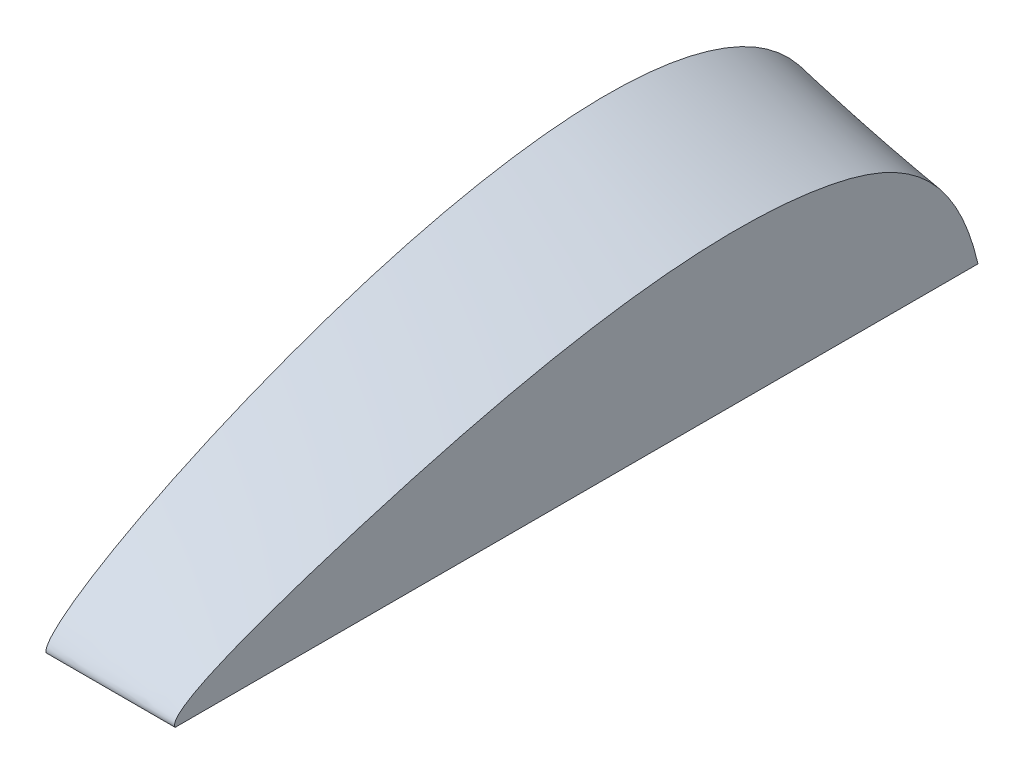
SolidWorks part; units mm, degrees
ref_plane "Front Plane" through (0, 0, 0) normal (0, 0, 1) x (1, 0, 0)
ref_plane "Top Plane" through (0, 0, 0) normal (0, 1, 0) x (1, 0, 0)
ref_plane "Right Plane" through (0, 0, 0) normal (1, 0, 0) x (0, 0, -1)
sketch "Sketch1" plane through (0, 0, 0) normal (1, 0, 0) x (0, 0, -1)
  line L0 (-142.24, 0) -> (142.24, 0)
  spline S0 degree 3 poles (-142.24, 0) (-145.7744, 14.133) (66.6053, 119.0753) (136.737, 38.6901) (142.24, 0) knots 0 0 0 0 0.781047 1 1 1 1
  point P3 (0, 0)
  point P5 (38.0226, 71.12)
  point P7 (38.0226, 0)
  point P8 (0, 0)
  point P9 (0, 0)
  point P10 (0, 0)
  point P11 (-53.3202, 49.8411)
  point P12 (67.1322, 64.4837)
  point P13 (-79.8162, 40.951)
  point P14 (52.664, 69.1902)
  point P15 (86.8299, 61.1717)
  point P16 (76.371, 66.04)
  point P17 (0, 0)
  point P18 (-87.6604, 34.1527)
  point P19 (51.2695, 66.04)
  point P20 (83.7485, 60.9782)
  point P21 (95.72, 60.8231)
  point P22 (87.0042, 60.9974)
  point P23 (88.3988, 71.6307)
  point P24 (101.6468, 65.7039)
  point P25 (101.6468, 65.7039)
  point P26 (72.1874, 71.9793)
  point P27 (47.2602, 71.12)
  point P28 (-82.2566, 37.639)
  point P29 (0, 0)
  point P30 (99.2064, 65.0066)
  dimension "D1" = 284.48
  dimension "D2" = 71.12
ref_plane "Plane1" through (45.72, 0, 0) normal (1, 0, 0) x (0, 0, -1)
sketch "Sketch2" plane through (45.72, 0, 0) normal (1, 0, 0) x (0, 0, -1)
  line L0 (-142.24, 0) -> (142.24, 0)
  spline S0 degree 3 poles (-142.24, 0) (-145.253, 5.7406) (-72.0439, 33.3646) (72.1826, 67.0992) (133.93, 35.685) (142.24, 0) knots 0 0 0 0 0.324251 0.769722 1 1 1 1
  point P2 (0, 0)
  point P4 (20.287, 50.8)
  point P6 (20.287, 0)
  point P8 (96.7134, 50.8)
  point P9 (-77.7712, 30.0334)
  point P10 (-83.9275, 27.1344)
  point P11 (0, 0)
  point P12 (-85.9041, 25.1421)
  point P13 (-92.3637, 24.0116)
  point P14 (0, 0)
  point P15 (-93.4942, 23.5272)
  point P16 (0, 0)
  point P17 (0, 0)
  point P18 (86.084, 50.8)
  point P19 (92.2206, 50.8)
  point P20 (87.6989, 50.8)
  dimension "D1" = 284.48
  dimension "D2" = 50.8
loft "Loft1" add profiles "Sketch1", "Sketch2"
